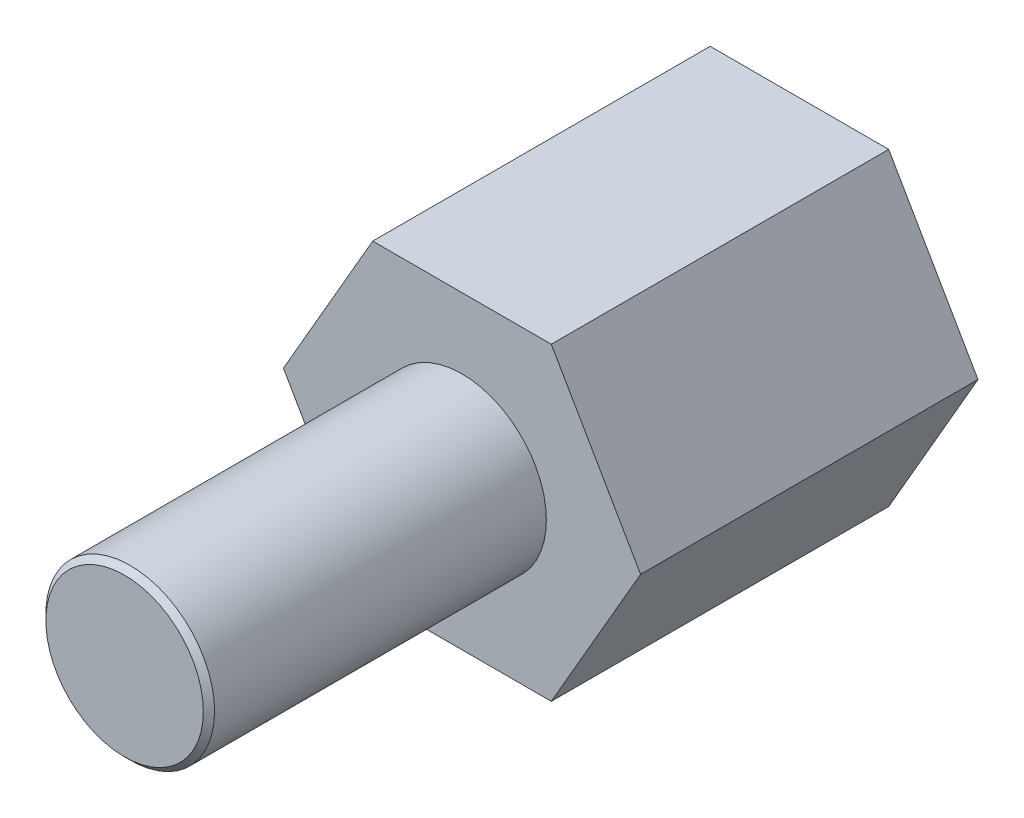
SolidWorks part; units mm, degrees
ref_plane "前视基准面" through (0, 0, 0) normal (0, 0, 1) x (1, 0, 0)
ref_plane "上视基准面" through (0, 0, 0) normal (0, 1, 0) x (1, 0, 0)
ref_plane "右视基准面" through (0, 0, 0) normal (1, 0, 0) x (0, 0, -1)
sketch "草图1" plane through (0, 0, 0) normal (0, 0, 1) x (1, 0, 0)
  line L1 (1.5877, 2.75) -> (-1.5877, 2.75)
  line L2 (-1.5877, 2.75) -> (-3.1754, 0)
  line L3 (-3.1754, 0) -> (-1.5877, -2.75)
  line L4 (-1.5877, -2.75) -> (1.5877, -2.75)
  line L5 (1.5877, -2.75) -> (3.1754, 0)
  line L6 (3.1754, 0) -> (1.5877, 2.75)
  circle A0 centre (0, 0) radius 2.75 construction
  dimension "D1" = 5.5
extrude "凸台-拉伸1" add sketch "草图1" along normal blind 6
sketch "草图2" plane through (0, 0, 6) normal (0, 0, 1) x (1, 0, 0)
  circle A0 centre (0, 0) radius 1.5
  dimension "D1" = 3
extrude "凸台-拉伸2" add sketch "草图2" along normal blind 6
hole_wizard "M3 螺纹孔1" positions "草图3" profile "草图5" tap size "M3" standard "GB"
sketch "草图3" plane through (0, 0, 0) normal (0, 0, -1) x (-1, 0, 0)
  point P0 (0, 0)
sketch "草图5" plane through (0, 0, 0) normal (1, 0, 0) x (0, 1, 0)
  line L0 (0, 0) -> (0, 4.7511)
  line L1 (0, 4.7511) -> (1.25, 4)
  line L2 (1.25, 4) -> (1.25, 0)
  line L5 (1.25, 0) -> (0, 0)
  line L10 (0, 4.7511) -> (-1.25, 4) construction
  line L11 (0, -6.35) -> (0, 107.95) construction
  dimension "螺纹孔钻头直径" = 2.5
  dimension "螺纹孔钻头深度" = 4
  dimension "导头角度" = 118
cosmetic thread "孔螺蚊线1" parameters "D1"=4, "D2"=3
chamfer "倒角1" distance 0.1 angle 45 1 edges at (1.5, 0, 12)
